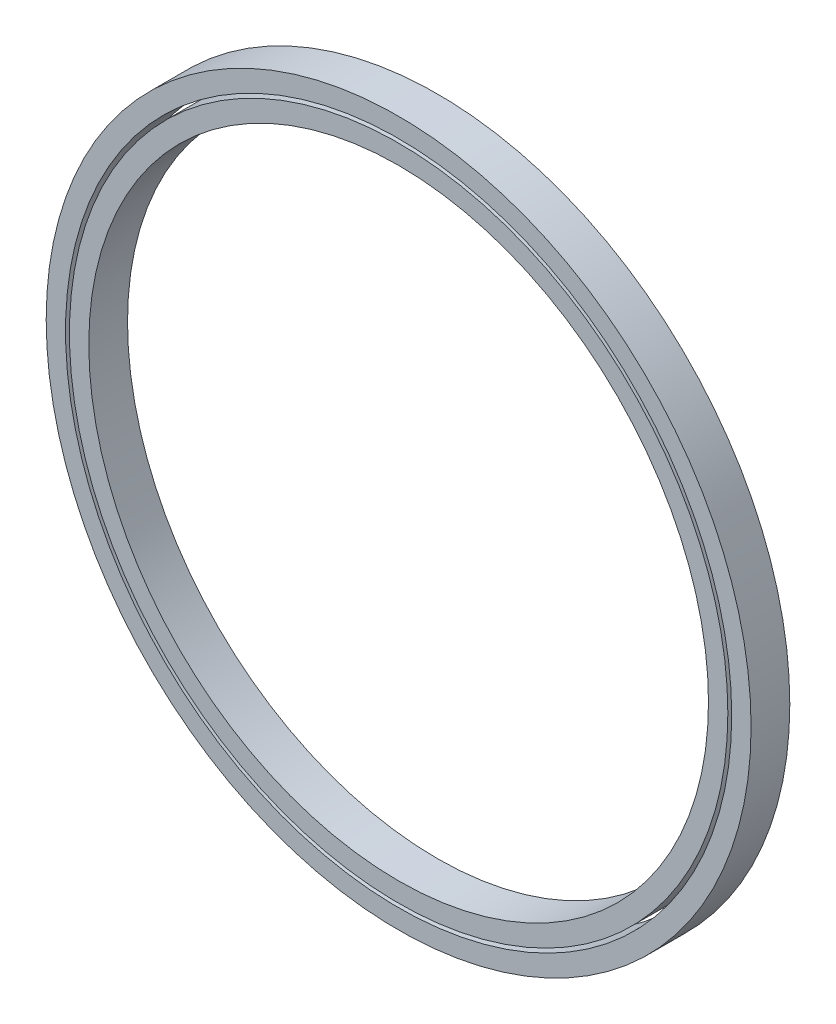
SolidWorks part; units mm, degrees
material "Plain Carbon Steel"
ref_plane "XY" through (0, 0, 0) normal (0, 0, 1) x (1, 0, 0)
ref_plane "XZ" through (0, 0, 0) normal (0, 1, 0) x (1, 0, 0)
ref_plane "YZ" through (0, 0, 0) normal (1, 0, 0) x (0, 0, -1)
sketch "Sketch1" plane through (0, 0, 0) normal (0, 0, 1) x (1, 0, 0)
  line L0 (40, 0) -> (45.5, 0) construction
  line L1 (42.5, 0) -> (43, 0) construction
  circle A0 centre (0, 0) radius 40
  circle A1 centre (0, 0) radius 42.5
  circle A2 centre (0, 0) radius 43
  circle A3 centre (0, 0) radius 45.5
  point P10 (42.75, 0)
  dimension "D1" = 80
  dimension "D2" = 5.5
  dimension "D3" = 0.5
extrude "Boss-Extrude1" add sketch "Sketch1" along normal mid plane 5 contours A1 A0 | A3 A2
